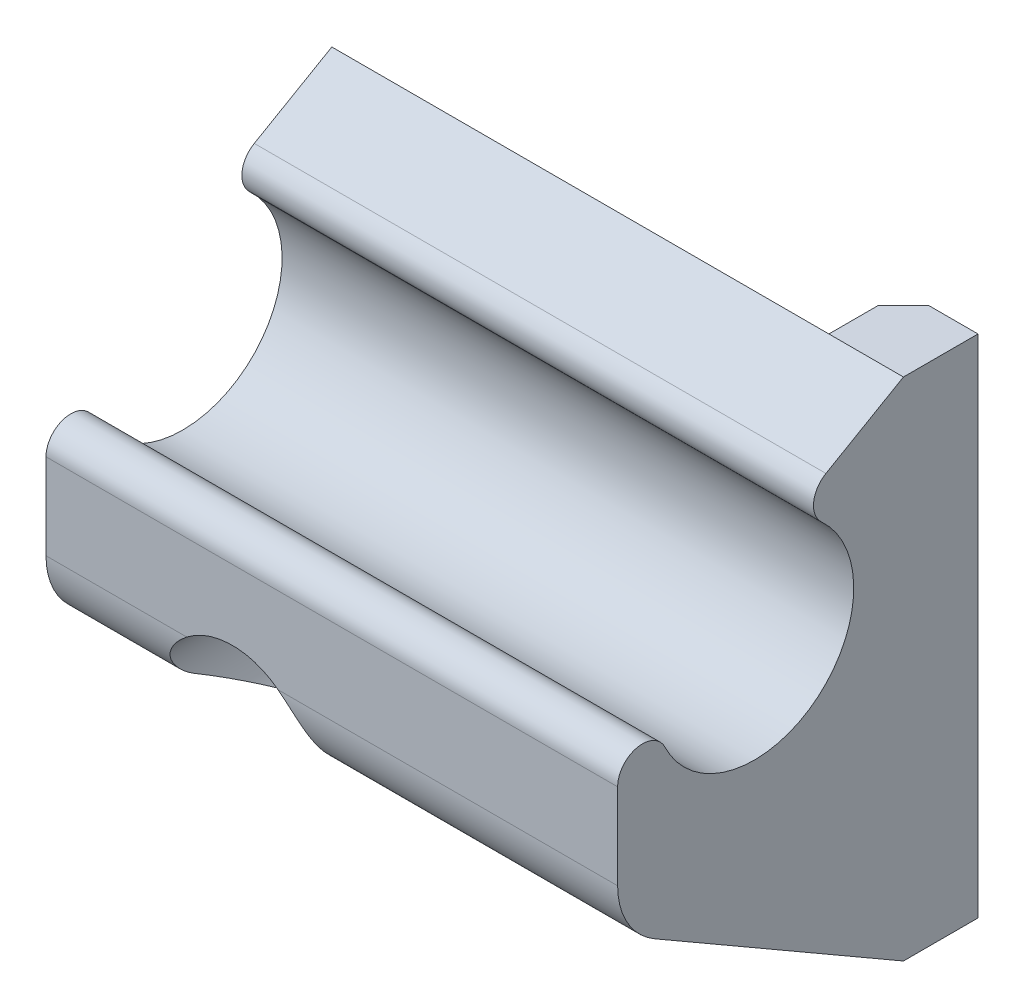
SolidWorks part; units mm, degrees
ref_plane "前视基准面" through (0, 0, 0) normal (0, 0, 1) x (1, 0, 0)
ref_plane "上视基准面" through (0, 0, 0) normal (0, 1, 0) x (1, 0, 0)
ref_plane "右视基准面" through (0, 0, 0) normal (1, 0, 0) x (0, 0, -1)
sketch "草图1" plane through (0, 0, 0) normal (1, 0, 0) x (0, 0, -1)
  line L0 (0, 0) -> (0, 14.3509)
  line L1 (0, 14.3509) -> (-3.1193, 12.5499)
  line L2 (0, 0) -> (0, -6)
  line L3 (0, -6) -> (-11.5, 0.6395)
  line L4 (-11.5, 0.6395) -> (-11.5, 5.8206)
  line L5 (-9.6, 6.2564) -> (-2.4, 9.7436) construction
  line L6 (0, 0) -> (-11.5, 0) construction
  arc A0 (-9.6, 6.2564) -> (-3.2955, 10.9471) centre (-6, 8) ccw
  arc A1 (-9.6, 6.2564) -> (-11.5, 5.8206) centre (-10.5, 5.8206) ccw
  arc A2 (-3.1193, 12.5499) -> (-3.2955, 10.9471) centre (-2.6193, 11.6839) ccw
  dimension "D1" = 8
  dimension "D2" = 8
  dimension "D4" = 6
  dimension "D5" = 5.5
  dimension "D6" = 1
  dimension "D7" = 1
  dimension "D3" = 2.5
  dimension "D8" = 60
  dimension "D9" = 6
  dimension "D10" = 60
extrude "凸台-拉伸1" add sketch "草图1" along normal blind 15.5 and the other way blind 7.5
sketch "草图2" plane through (0, 0, 11.5) normal (0, 0, 1) x (1, 0, 0)
  circle A0 centre (0, 0) radius 1.6
  dimension "D1" = 3.2
extrude "切除-拉伸1" cut sketch "草图2" against normal through all
sketch "草图3" plane through (0, 0, 11.5) normal (0, 0, 1) x (1, 0, 0)
  circle A0 centre (0, 0) radius 3
  dimension "D1" = 6
extrude "切除-拉伸2" cut sketch "草图3" against normal blind 6
sketch "草图4" plane through (0, 0, 0) normal (0, 0, -1) x (-1, 0, 0)
  line L0 (7.5, -6) -> (-15.5, -6) construction
  line L1 (-12.5, 14.3509) -> (-15.5, 14.3509)
  line L2 (-12.5, 14.3509) -> (-12.5, -6)
  line L3 (-12.5, -6) -> (-15.5, -6)
  line L4 (-15.5, 14.3509) -> (-15.5, -6)
  dimension "D1" = 3
extrude "凸台-拉伸2" add sketch "草图4" along normal blind 3
fillet "圆角1" radius 3 2 edges at (9.2155, 0.6395, 11.5) (-5.2155, 0.6395, 11.5)
chamfer "倒角2" distance 1 angle 45 1 edges at (12.5, 4.1754, -3)
